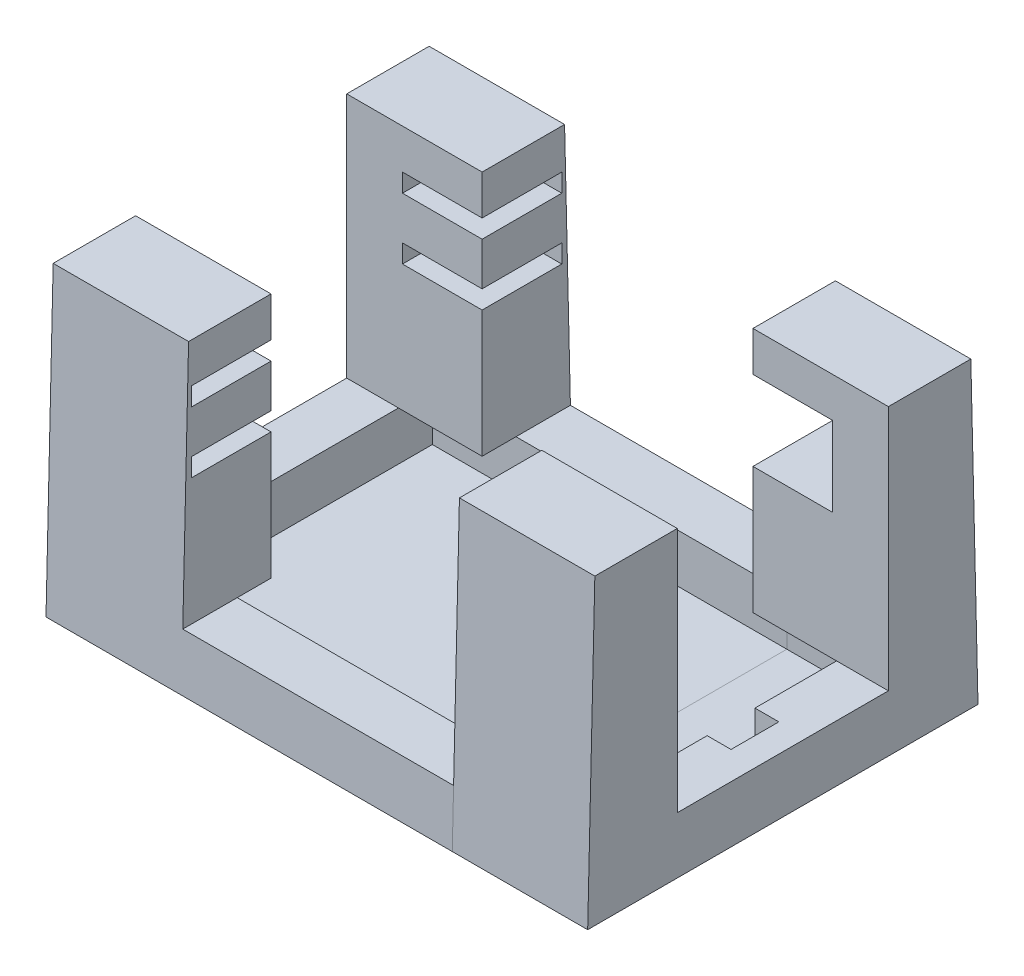
SolidWorks part; units mm, degrees
ref_plane "Front Plane" through (0, 0, 0) normal (0, 0, 1) x (1, 0, 0)
ref_plane "Top Plane" through (0, 0, 0) normal (0, 1, 0) x (1, 0, 0)
ref_plane "Right Plane" through (0, 0, 0) normal (1, 0, 0) x (0, 0, -1)
sketch "Sketch3" plane through (0, 0, 0) normal (0, 1, 0) x (1, 0, 0)
  line L1 (34, -24.5) -> (-34, -24.5)
  line L2 (34, -24.5) -> (34, 24.5)
  line L3 (34, 24.5) -> (-34, 24.5)
  line L4 (-34, -24.5) -> (-34, 24.5)
  line L5 (34, -24.5) -> (-34, 24.5) construction
  line L6 (34, 24.5) -> (-34, -24.5) construction
  point P0 (0, 0)
  dimension "D1" = 68
  dimension "D2" = 49
extrude "Boss-Extrude1" add sketch "Sketch3" along normal blind 7.1
sketch "Sketch6" plane through (0, 0, 0) normal (0, -1, 0) x (1, 0, 0)
  line L1 (34, 24.5) -> (17, 24.5)
  line L2 (34, 24.5) -> (34, 13.25)
  line L3 (34, 13.25) -> (17, 13.25)
  line L4 (17, 24.5) -> (17, 13.25)
  line L5 (-34, 24.5) -> (-17, 24.5)
  line L6 (-34, 24.5) -> (-34, 13.25)
  line L7 (-34, 13.25) -> (-17, 13.25)
  line L8 (-17, 24.5) -> (-17, 13.25)
  line L9 (-34, -24.5) -> (-17, -24.5)
  line L10 (-34, -24.5) -> (-34, -13.25)
  line L11 (-34, -13.25) -> (-17, -13.25)
  line L12 (-17, -24.5) -> (-17, -13.25)
  line L13 (34, -24.5) -> (17, -24.5)
  line L14 (34, -24.5) -> (34, -13.25)
  line L15 (34, -13.25) -> (17, -13.25)
  line L16 (17, -24.5) -> (17, -13.25)
  dimension "D1" = 11.25
  dimension "D2" = 17
  dimension "D3" = 17
  dimension "D4" = 17
  dimension "D5" = 11.25
  dimension "D6" = 11.25
  dimension "D7" = 11.25
  dimension "D8" = 17
extrude "Boss-Extrude2" add sketch "Sketch6" against normal blind 38
sketch "Sketch7" plane through (34, 0, 0) normal (1, 0, 0) x (0, 0, -1)
  line L0 (-13.25, 38) -> (-24.5, 38) construction
  line L1 (-23.25, 33) -> (23.25, 33)
  line L2 (-23.25, 33) -> (-23.25, 23)
  line L3 (-23.25, 23) -> (23.25, 23)
  line L4 (23.25, 33) -> (23.25, 23)
  line L5 (-24.5, 38) -> (-24.5, 0) construction
  dimension "D1" = 5
  dimension "D2" = 10
  dimension "D3" = 46.5
  dimension "D4" = 1.25
extrude "Cut-Extrude2" cut sketch "Sketch7" against normal up to next from offset 7
sketch "Sketch9" plane through (-34, 0, 0) normal (-1, 0, 0) x (0, 0, 1)
  line L1 (23.25, 33) -> (23.25, 23) construction
  line L2 (-23.25, 23) -> (23.25, 23)
  line L3 (-23.25, 23) -> (-23.25, 33)
  line L4 (-23.25, 33) -> (23.25, 33)
  line L9 (23.25, 23) -> (23.25, 33)
  line L10 (-23.25, 23) -> (-23.25, 33) construction
  line L11 (-23.25, 33) -> (-13.25, 33) construction
  line L12 (23.25, 23) -> (13.25, 23) construction
extrude "Cut-Extrude3" cut sketch "Sketch9" against normal up to next from offset 7
sketch "Sketch10" plane through (-34, 0, 0) normal (-1, 0, 0) x (0, 0, 1)
  line L0 (24.5, 38) -> (24.5, 0) construction
  line L1 (24.5, 30.7) -> (13.25, 30.7)
  line L2 (24.5, 30.7) -> (24.5, 25.3)
  line L3 (24.5, 25.3) -> (13.25, 25.3)
  line L4 (-24.5, 30.7) -> (-24.5, 25.3)
  line L5 (-24.5, 38) -> (-24.5, 0) construction
  line L6 (24.5, 38) -> (13.25, 38) construction
  line L7 (-13.25, 25.3) -> (-13.25, 30.7)
  line L8 (-13.25, 38) -> (-13.25, 7.1) construction
  line L9 (13.25, 30.7) -> (13.25, 25.3)
  line L10 (13.25, 38) -> (13.25, 7.1) construction
  line L11 (-13.25, 30.7) -> (-24.5, 30.7)
  line L12 (-13.25, 25.3) -> (-24.5, 25.3)
  dimension "D1" = 7.3
  dimension "D2" = 5.4
extrude "Boss-Extrude3" add sketch "Sketch10" against normal up to surface (17 mm away) up to face at (-17, 25.275, -18.5625)
sketch "Sketch11" plane through (0, 0, 0) normal (0, -1, 0) x (1, 0, 0)
  line L1 (27.5, -17.5) -> (-27.5, -17.5)
  line L2 (27.5, -17.5) -> (27.5, 17.5)
  line L3 (27.5, 17.5) -> (-27.5, 17.5)
  line L4 (-27.5, -17.5) -> (-27.5, 17.5)
  line L5 (27.5, -17.5) -> (-27.5, 17.5) construction
  line L6 (27.5, 17.5) -> (-27.5, -17.5) construction
  point P0 (0, 0)
  dimension "D1" = 55
  dimension "D2" = 35
extrude "Cut-Extrude4" cut sketch "Sketch11" against normal up to surface (6.1 mm away) from offset 1 up to face at (0, 7.1, 0) offset against normal yes
sketch "Sketch12" plane through (0, 0, 0) normal (0, -1, 0) x (1, 0, 0)
  line L0 (27.5, -17.5) -> (27.5, 17.5) construction
  line L1 (30.5, -3) -> (27.5, -3)
  line L2 (30.5, -3) -> (30.5, 3)
  line L3 (30.5, 3) -> (27.5, 3)
  line L4 (27.5, -3) -> (27.5, 3)
  line L5 (30.5, -3) -> (27.5, 3) construction
  line L6 (30.5, 3) -> (27.5, -3) construction
  point P0 (29, 0)
  dimension "D1" = 3
  dimension "D2" = 6
extrude "Cut-Extrude5" cut sketch "Sketch12" against normal up to next
ref_plane "Plane2" through (17, 0, 0) normal (1, 0, 0) x (0, 0, -1)
sketch "Sketch13" plane through (34, 0, 0) normal (1, 0, 0) x (0, 0, -1)
  line L0 (-24.5, 0) -> (-23.6, 38)
  line L1 (-13.25, 38) -> (-24.5, 38) construction
  line L2 (-23.6, 38) -> (-24.5, 38)
  line L3 (-24.5, 38) -> (-24.5, 0)
  line L5 (0, -3.7394) -> (0, 42.714) construction
  line L6 (24.5, 0) -> (23.6, 38)
  line L7 (23.6, 38) -> (24.5, 38)
  line L8 (24.5, 38) -> (24.5, 0)
  dimension "D1" = 0.9
sketch "Sketch14" plane through (34, 0, 0) normal (1, 0, 0) x (0, 0, -1)
sketch "Sketch17" plane through (34, 0, 0) normal (1, 0, 0) x (0, 0, -1)
extrude "Cut-Extrude9" cut sketch "Sketch13" against normal through all
split "Split1" trim tools "Plane2" bodies to split 121 resulting bodies 122 123
sketch "Sketch18" plane through (0, 7.1, 0) normal (0, 1, 0) x (1, 0, 0)
  line L0 (30.5, 13.25) -> (34, 13.25)
  line L1 (34, 13.25) -> (17, 13.25) construction
  line L2 (34, 13.25) -> (34, -13.25)
  line L3 (34, -13.25) -> (30.5, -13.25)
  line L4 (34, -13.25) -> (27.5, -13.25) construction
  line L5 (30.5, -13.25) -> (30.5, 13.25)
  line L6 (30.5, 13.25) -> (30.4998, 13.2398)
equation "\"length\"= 6.8"
equation "\"D1@Sketch3\"=\"length\""
equation "\"width_bottom\"= 4.9"
equation "\"D2@Sketch3\"=\"width_bottom\""
equation "\"height\"= 3.8"
equation "\"w_bat\"= 3.5"
equation "\"l_bat\"= 5.5"
equation "\"h_bat\"=0.71"
equation "\"w_module\"= 4.65"
equation "\"l_module\"= 5.4"
equation "\"h_module\"= 1"
equation "\"t_board\"= .23"
equation "\"h_clear\"= 0.5"
equation "\"D1@Boss-Extrude1\"=\"h_bat\""
equation "\"w_leg\"= ( \"width_bottom\" - \"w_module\" + 2 ) / 2"
equation "\"l_leg\"= ( \"length\" - \"l_module\" + 2 ) / 2"
equation "\"D1@Sketch6\"=\"w_leg\""
equation "\"D2@Sketch6\"=\"l_leg\""
equation "\"D3@Sketch6\"=\"l_leg\""
equation "\"D4@Sketch6\"=\"l_leg\""
equation "\"D5@Sketch6\"=\"w_leg\""
equation "\"D6@Sketch6\"=\"w_leg\""
equation "\"D7@Sketch6\"=\"w_leg\""
equation "\"D8@Sketch6\"=\"l_leg\""
equation "\"D1@Boss-Extrude2\"=\"height\""
equation "\"D1@Sketch7\"=\"h_clear\""
equation "\"D2@Sketch7\"=\"h_module\""
equation "\"D3@Sketch7\"=\"w_module\""
equation "\"D4@Sketch7\"=(\"width_bottom\"-\"w_module\")/2"
equation "\"D19@Cut-Extrude2\"=(\"length\"-\"l_module\")/2"
equation "\"D19@Cut-Extrude3\"=(\"length\"-\"l_module\")/2"
equation "\"D1@Sketch10\"=\"h_clear\" + \"t_board\""
equation "\"D2@Sketch10\"=\"h_module\"-2 * \"t_board\""
equation "\"D1@Sketch11\"=\"l_bat\""
equation "\"D2@Sketch11\"=\"w_bat\""
equation "\"inset_top\"= 0.09"
equation "\"D1@Sketch13\"=\"inset_top\""
